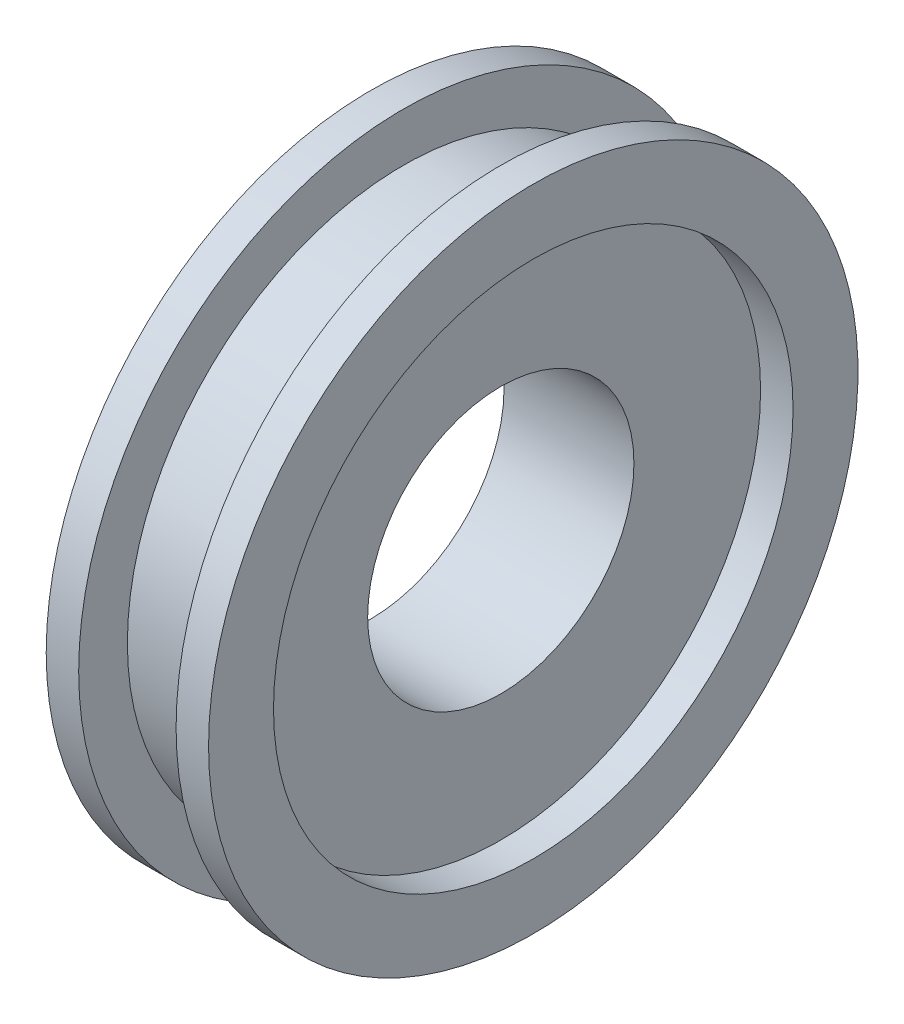
SolidWorks part; units mm, degrees
ref_plane "Front Plane" through (0, 0, 0) normal (0, 0, 1) x (1, 0, 0)
ref_plane "Top Plane" through (0, 0, 0) normal (0, 1, 0) x (1, 0, 0)
ref_plane "Right Plane" through (0, 0, 0) normal (1, 0, 0) x (0, 0, -1)
sketch "Sketch1" plane through (0, 0, 0) normal (0, 0, 1) x (1, 0, 0)
  line L0 (0, 0) -> (5.1881, 0) construction
  line L2 (-5.5, -0.875) -> (-5.5, 10) construction
  line L3 (-5.5, 10) -> (-0.5, 10)
  line L4 (-0.5, 4.1) -> (-0.5, 10)
  line L5 (-5.5, 10) -> (-5.5, 4.1)
  line L8 (-5.5, 4.1) -> (-0.5, 4.1)
  dimension "D1" = 10
  dimension "D2" = 5
  dimension "D5" = 4.1
revolve "Revolve1" add sketch "Sketch1" angle 360 about L0
sketch "Sketch2" plane through (0, 0, 0) normal (0, 0, 1) x (1, 0, 0)
  line L6 (0, 0) -> (5.4705, 0) construction
  line L9 (-0.5, 3.3693) -> (-0.5, 10) construction
  line L10 (-0.5, 10) -> (-1.5, 10) construction
  line L11 (-1.5, 10) -> (-1.5, 8.5) construction
  line L12 (-1.5, 8.5) -> (-5.5, 8.5) construction
  line L13 (-5.5, 8.5) -> (-5.5, 3.3693) construction
  line L14 (-0.5, 10) -> (-5.5, 10) construction
  line L15 (-0.5, -10) -> (-0.5, 10) construction
  line L16 (-5.5, 10) -> (-5.5, -10) construction
  line L17 (-1.5, 8.5) -> (-1.5, 10)
  line L18 (-1.5, 10) -> (-4.5, 10)
  line L20 (-4.5, 10) -> (-4.5, 8.5)
  line L21 (-4.5, 8.5) -> (-1.5, 8.5)
  line L22 (-4.5, 10) -> (-5.5, 10) construction
  line L23 (-1.5, 10) -> (-0.5, 10) construction
  dimension "D1" = 8.5
  dimension "D2" = 3
  dimension "D3" = 1
  dimension "D5" = 1.5
revolve "Cut-Revolve1" cut sketch "Sketch2" angle 360 about L6
sketch "Sketch3" plane through (0, 0, 0) normal (1, 0, 0) x (0, 0, -1)
  circle A0 centre (0, 0) radius 8
  dimension "D1" = 16
extrude "Cut-Extrude1" cut sketch "Sketch3" against normal blind 1.5
sketch "Sketch5" plane through (-5.5, 0, 0) normal (-1, 0, 0) x (0, 0, 1)
  text T0 "<b>16</b>"
  point P1 (0, 0)
  point P2 (0, 0)
extrude "Cut-Extrude2" cut sketch "Sketch5" against normal blind 1.5
